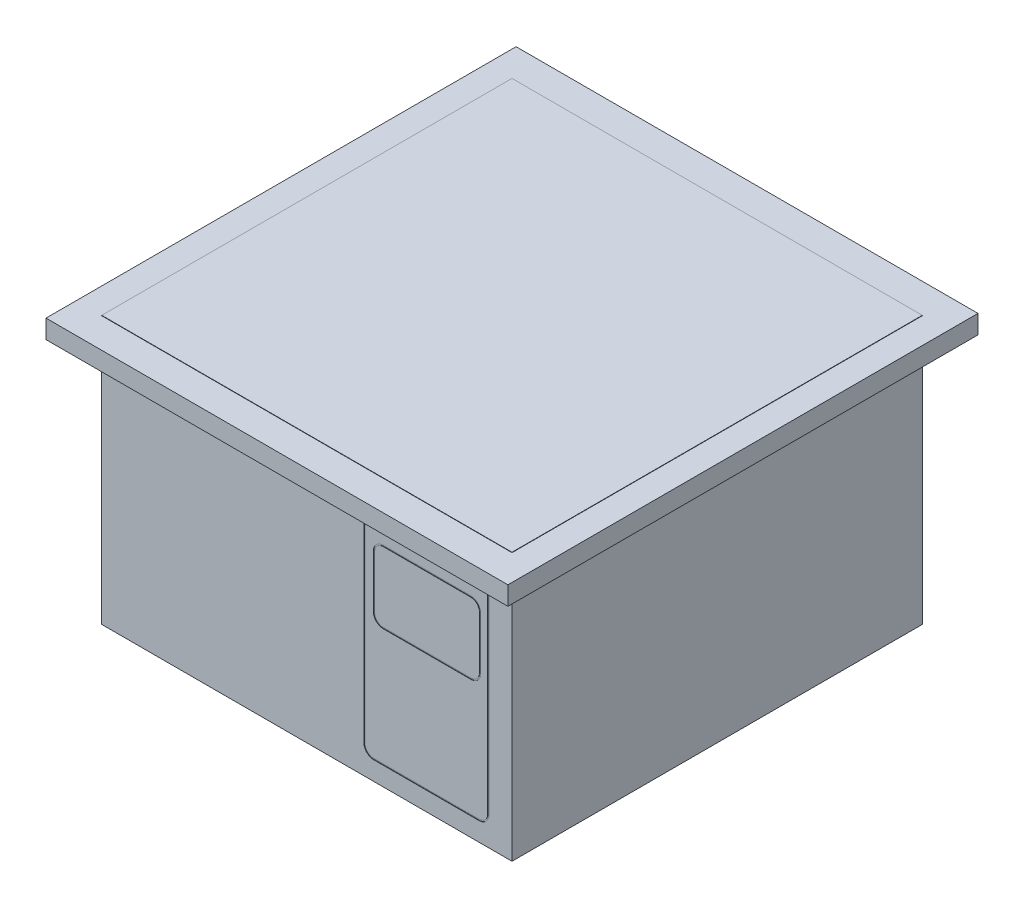
SolidWorks part; units mm, degrees
ref_plane "Alzado" through (0, 0, 0) normal (0, 0, 1) x (1, 0, 0)
ref_plane "Planta" through (0, 0, 0) normal (0, 1, 0) x (1, 0, 0)
ref_plane "Vista lateral" through (0, 0, 0) normal (1, 0, 0) x (0, 0, -1)
sketch "Croquis1" plane through (0, 0, 0) normal (0, 1, 0) x (1, 0, 0)
  line L0 (-1500, 1500) -> (-1500, -1500)
  line L1 (-1650, 1650) -> (1650, 1650)
  line L2 (-1650, 1650) -> (-1650, -1650)
  line L3 (-1650, -1650) -> (1650, -1650)
  line L4 (1650, 1650) -> (1650, -1650)
  line L5 (-1650, 1650) -> (1650, -1650) construction
  line L6 (-1650, -1650) -> (1650, 1650) construction
  line L7 (-1500, -1500) -> (1500, -1500)
  line L8 (1500, 1500) -> (1500, -1500)
  line L9 (-1500, 1500) -> (1500, 1500)
  point P0 (0, 0)
  dimension "D1" = 3300
  dimension "D2" = 3300
  dimension "D3" = 150
extrude "Saliente-Extruir1" add sketch "Croquis1" along normal blind 2000
sketch "Croquis2" plane through (0, 2000, 0) normal (0, 1, 0) x (1, 0, 0)
  line L1 (-1857.5539, -1890.4617) -> (1857.5539, -1890.4617)
  line L2 (-1857.5539, -1890.4617) -> (-1857.5539, 1890.4617)
  line L3 (-1857.5539, 1890.4617) -> (1857.5539, 1890.4617)
  line L4 (1857.5539, -1890.4617) -> (1857.5539, 1890.4617)
  line L5 (-1857.5539, -1890.4617) -> (1857.5539, 1890.4617) construction
  line L6 (-1857.5539, 1890.4617) -> (1857.5539, -1890.4617) construction
  line L7 (-1650, 1650) -> (1650, 1650)
  line L8 (-1650, 1650) -> (-1650, -1650)
  line L9 (-1650, -1650) -> (1650, -1650)
  line L10 (1650, 1650) -> (1650, -1650)
  line L11 (-1650, 1650) -> (1650, -1650) construction
  line L12 (-1650, -1650) -> (1650, 1650) construction
  point P0 (0, 0)
  point P6 (0, 0)
extrude "Saliente-Extruir2" add sketch "Croquis2" along normal blind 150 separate body
sketch "Croquis3" plane through (0, 0, 1650) normal (0, 0, 1) x (1, 0, 0)
  line L0 (458.6934, 1745.1353) -> (458.6934, 231.1014)
  line L1 (538.6934, 1815.1353) -> (1384.4613, 1815.1353)
  line L2 (468.6934, 1745.1353) -> (468.6934, 231.1014)
  line L3 (538.6934, 161.1014) -> (1384.4613, 161.1014)
  line L4 (1454.4613, 1745.1353) -> (1454.4613, 231.1014)
  line L5 (468.6934, 1815.1353) -> (1454.4613, 161.1014) construction
  line L6 (468.6934, 161.1014) -> (1454.4613, 1815.1353) construction
  line L7 (538.6934, 151.1014) -> (1384.4613, 151.1014)
  line L8 (1464.4613, 1745.1353) -> (1464.4613, 231.1014)
  line L9 (538.6934, 1825.1353) -> (1384.4613, 1825.1353)
  arc A0 (468.6934, 231.1014) -> (538.6934, 161.1014) centre (538.6934, 231.1014) ccw
  arc A1 (1384.4613, 161.1014) -> (1454.4613, 231.1014) centre (1384.4613, 231.1014) ccw
  arc A2 (1384.4613, 1815.1353) -> (1454.4613, 1745.1353) centre (1384.4613, 1745.1353) cw
  arc A3 (538.6934, 1815.1353) -> (468.6934, 1745.1353) centre (538.6934, 1745.1353) ccw
  arc A4 (458.6934, 231.1014) -> (538.6934, 151.1014) centre (538.6934, 231.1014) ccw
  arc A5 (1384.4613, 151.1014) -> (1464.4613, 231.1014) centre (1384.4613, 231.1014) ccw
  arc A6 (1384.4613, 1825.1353) -> (1464.4613, 1745.1353) centre (1384.4613, 1745.1353) cw
  arc A7 (538.6934, 1825.1353) -> (458.6934, 1745.1353) centre (538.6934, 1745.1353) ccw
  point P0 (961.5773, 988.1184)
  dimension "D1" = 70
  dimension "D2" = 10
extrude "Cortar-Extruir1" cut sketch "Croquis3" against normal blind 3
sketch "Croquis4" plane through (0, 0, 1650) normal (0, 0, 1) x (1, 0, 0)
  line L0 (535.2428, 1604.1703) -> (535.2428, 1181.9157)
  line L1 (615.2428, 1674.1703) -> (1318.6248, 1674.1703)
  line L2 (545.2428, 1604.1703) -> (545.2428, 1181.9157)
  line L3 (615.2428, 1111.9157) -> (1318.6248, 1111.9157)
  line L4 (1388.6248, 1604.1703) -> (1388.6248, 1181.9157)
  line L5 (545.2428, 1674.1703) -> (1388.6248, 1111.9157) construction
  line L6 (545.2428, 1111.9157) -> (1388.6248, 1674.1703) construction
  line L7 (615.2428, 1101.9157) -> (1318.6248, 1101.9157)
  line L8 (1398.6248, 1604.1703) -> (1398.6248, 1181.9157)
  line L9 (615.2428, 1684.1703) -> (1318.6248, 1684.1703)
  arc A0 (545.2428, 1181.9157) -> (615.2428, 1111.9157) centre (615.2428, 1181.9157) ccw
  arc A1 (1318.6248, 1111.9157) -> (1388.6248, 1181.9157) centre (1318.6248, 1181.9157) ccw
  arc A2 (1318.6248, 1674.1703) -> (1388.6248, 1604.1703) centre (1318.6248, 1604.1703) cw
  arc A3 (615.2428, 1674.1703) -> (545.2428, 1604.1703) centre (615.2428, 1604.1703) ccw
  arc A4 (535.2428, 1181.9157) -> (615.2428, 1101.9157) centre (615.2428, 1181.9157) ccw
  arc A5 (1318.6248, 1101.9157) -> (1398.6248, 1181.9157) centre (1318.6248, 1181.9157) ccw
  arc A6 (1318.6248, 1684.1703) -> (1398.6248, 1604.1703) centre (1318.6248, 1604.1703) cw
  arc A7 (615.2428, 1684.1703) -> (535.2428, 1604.1703) centre (615.2428, 1604.1703) ccw
  point P0 (966.9338, 1393.043)
  dimension "D1" = 70
  dimension "D2" = 10
extrude "Cortar-Extruir2" cut sketch "Croquis4" against normal blind 3
sketch "Croquis5" plane through (0, 2150, 0) normal (0, 1, 0) x (1, 0, 0)
  line L1 (-1650, 1650) -> (1650, 1650)
  line L2 (-1650, 1650) -> (-1650, -1650)
  line L3 (-1650, -1650) -> (1650, -1650)
  line L4 (1650, 1650) -> (1650, -1650)
  line L5 (-1650, 1650) -> (1650, -1650) construction
  line L6 (-1650, -1650) -> (1650, 1650) construction
  point P0 (0, 0)
extrude "Saliente-Extruir3" add sketch "Croquis5" along normal blind 3 separate body
